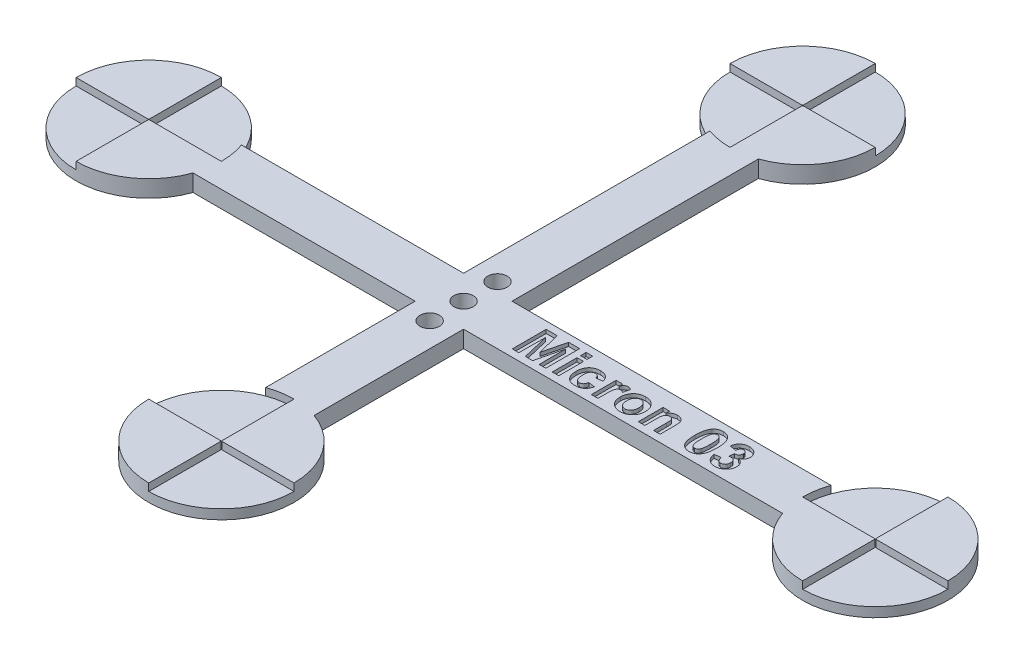
SolidWorks part; units mm, degrees
ref_plane "Front Plane" through (0, 0, 0) normal (0, 0, 1) x (1, 0, 0)
ref_plane "Top Plane" through (0, 0, 0) normal (0, 1, 0) x (1, 0, 0)
ref_plane "Right Plane" through (0, 0, 0) normal (1, 0, 0) x (0, 0, -1)
sketch "Sketch1" plane through (0, 0, 0) normal (0, 1, 0) x (1, 0, 0)
  line L0 (0, 0) -> (150, 0) construction
  line L1 (65, 70) -> (65, -50) construction
  line L2 (60, 55.8579) -> (60, 5)
  line L3 (70, 55.8579) -> (70, 5)
  line L4 (14.1421, 5) -> (60, 5)
  line L5 (14.1421, -5) -> (60, -5)
  line L6 (70, 5) -> (135.8579, 5)
  line L7 (60, -5) -> (60, -35.8579)
  line L8 (70, -5) -> (135.8579, -5)
  line L9 (70, -5) -> (70, -35.8579)
  arc A0 (14.1421, 5) -> (14.1421, -5) centre (0, 0) ccw
  arc A1 (135.8579, -5) -> (135.8579, 5) centre (150, 0) ccw
  arc A2 (70, 55.8579) -> (60, 55.8579) centre (65, 70) ccw
  arc A3 (60, -35.8579) -> (70, -35.8579) centre (65, -50) ccw
  dimension "D1" = 30
  dimension "D3" = 30
  dimension "D5" = 30
  dimension "D6" = 30
  dimension "D2" = 150
  dimension "D4" = 65
  dimension "D7" = 70
  dimension "D8" = 120
  dimension "D9" = 5
  dimension "D10" = 5
  dimension "D11" = 5
  dimension "D12" = 5
extrude "Boss-Extrude1" add sketch "Sketch1" along normal blind 3.5
sketch "Sketch2" plane through (0, 3.5, 0) normal (0, 1, 0) x (1, 0, 0)
  line L0 (65, -65) -> (65, -50.1)
  line L1 (-15, 0) -> (-0.1, 0)
  line L2 (50, 70) -> (64.9, 70)
  line L3 (0, 15) -> (0, 0.1)
  line L4 (150, 15) -> (150, 0.1)
  line L5 (50, -50) -> (64.9, -50)
  line L6 (65.1, 70) -> (80, 70)
  line L7 (65, 70.1) -> (65, 85)
  line L8 (65, 55) -> (65, 69.9)
  line L9 (65, -49.9) -> (65, -35)
  line L10 (65.1, -50) -> (80, -50)
  line L11 (135, 0) -> (149.9, 0)
  line L12 (0.1, 0) -> (15, 0)
  line L13 (0, -0.1) -> (0, -15)
  line L14 (150, -0.1) -> (150, -15)
  line L15 (150.1, 0) -> (165, 0)
  arc A0 (15, 0) -> (0, 15) centre (0, 0) ccw
  arc A1 (150, -15) -> (165, 0) centre (150, 0) ccw
  arc A2 (50, 70) -> (65, 55) centre (65, 70) ccw
  arc A3 (65, -35) -> (50, -50) centre (65, -50) ccw
  arc A4 (0, 0.1) -> (-0.1, 0) centre (0, 0) ccw
  arc A5 (65, 69.9) -> (65.1, 70) centre (65, 70) ccw
  arc A6 (149.9, 0) -> (150, -0.1) centre (150, 0) ccw
  arc A7 (64.9, -50) -> (65, -50.1) centre (65, -50) ccw
  arc A8 (65, 70.1) -> (64.9, 70) centre (65, 70) ccw
  arc A9 (80, 70) -> (65, 85) centre (65, 70) ccw
  arc A10 (65, -65) -> (80, -50) centre (65, -50) ccw
  arc A11 (65.1, -50) -> (65, -49.9) centre (65, -50) ccw
  arc A12 (-15, 0) -> (0, -15) centre (0, 0) ccw
  arc A13 (0, -0.1) -> (0.1, 0) centre (0, 0) ccw
  arc A14 (150.1, 0) -> (150, 0.1) centre (150, 0) ccw
  arc A15 (150, 15) -> (135, 0) centre (150, 0) ccw
  arc A16 (60, -35.8579) -> (70, -35.8579) centre (65, -50) ccw construction
  arc A17 (70, 55.8579) -> (60, 55.8579) centre (65, 70) ccw construction
  dimension "D1" = 0.2
  dimension "D2" = 0.2
  dimension "D3" = 0.2
  dimension "D4" = 0.2
extrude "Cut-Extrude1" cut sketch "Sketch2" against normal blind 1.52
sketch "Sketch3" plane through (0, 3.5, 0) normal (0, 1, 0) x (1, 0, 0)
  line L0 (65, -49.9) -> (65, -35) construction
  line L1 (65, 7) -> (65, -7) construction
  circle A0 centre (65, 0) radius 2
  circle A1 centre (65, 7) radius 2
  circle A2 centre (65, -7) radius 2
  point P2 (65, 0)
  dimension "D2" = 4
  dimension "D3" = 4
  dimension "D4" = 4
  dimension "D1" = 14
extrude "Cut-Extrude2" cut sketch "Sketch3" against normal through all
sketch "Sketch5" plane through (0, 3.5, 0) normal (0, 1, 0) x (1, 0, 0)
  line L0 (77.9289, -3.5) -> (127.9289, -3.5) construction
  line L1 (70, -5) -> (135.8579, -5) construction
  text T0 "Micron 03" font "Arial" height 7
  point P4 (102.9289, -3.5)
  point P5 (102.9289, -5)
  dimension "D1" = 1.5
  dimension "D2" = 50
extrude "Cut-Extrude3" cut sketch "Sketch5" against normal blind 0.75
